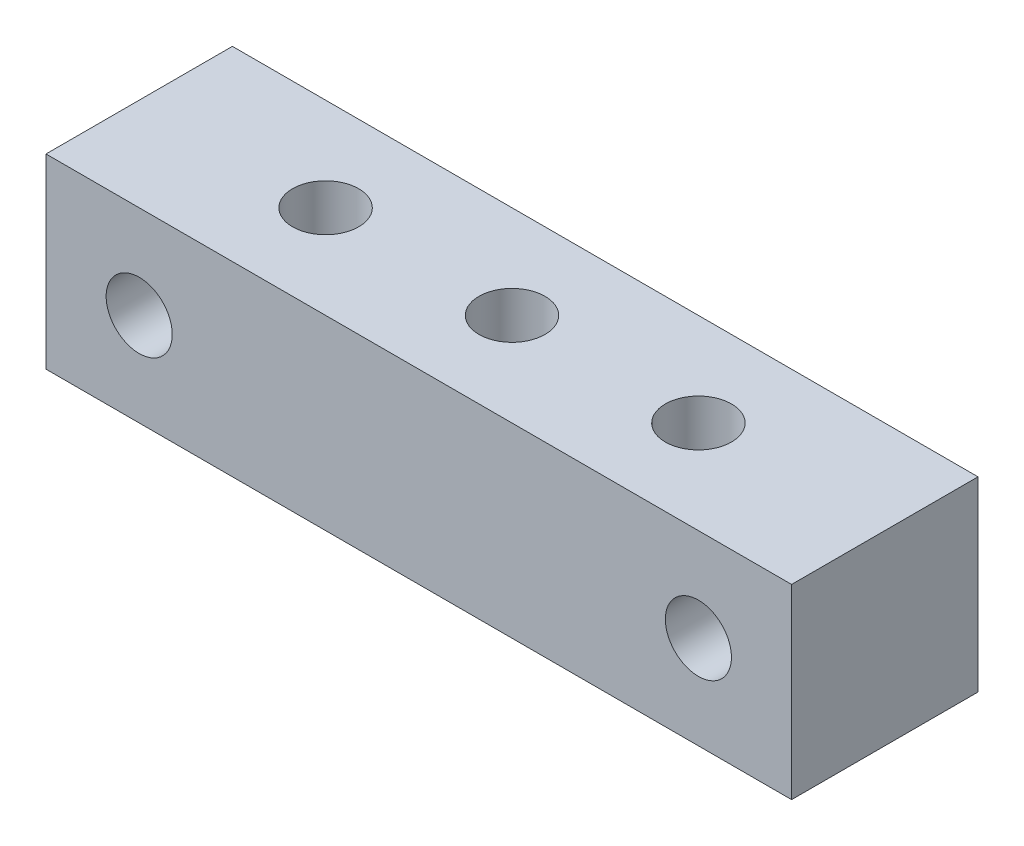
SolidWorks part; units mm, degrees
ref_plane "Front" through (0, 0, 0) normal (0, 0, 1) x (1, 0, 0)
ref_plane "Top" through (0, 0, 0) normal (0, 1, 0) x (1, 0, 0)
ref_plane "Right" through (0, 0, 0) normal (1, 0, 0) x (0, 0, -1)
sketch "Sketch1" plane through (0, 0, 0) normal (0, 0, 1) x (1, 0, 0)
  line L1 (-38.1, -9.525) -> (38.1, -9.525)
  line L2 (-38.1, -9.525) -> (-38.1, 9.525)
  line L3 (-38.1, 9.525) -> (38.1, 9.525)
  line L4 (38.1, -9.525) -> (38.1, 9.525)
  line L5 (-38.1, -9.525) -> (38.1, 9.525) construction
  line L6 (-38.1, 9.525) -> (38.1, -9.525) construction
  point P0 (0, 0)
  dimension "D1" = 19.05
  dimension "D2" = 76.2
extrude "Boss-Extrude1" add sketch "Sketch1" along normal blind 19.05
sketch "Sketch3" plane through (0, 0, 19.05) normal (0, 0, 1) x (1, 0, 0)
  line L1 (28.575, 0) -> (-28.575, 0) construction
  point P0 (0, 0)
  point P4 (0, 0)
  dimension "D2" = 57.15
hole_wizard "1/4 Clearance Hole1" positions "Sketch7" profile "Sketch6" hole size "1/4" standard "ANSI Inch" end condition through all
sketch "Sketch7" plane through (0, 0, 19.05) normal (0, 0, 1) x (1, 0, 0)
  point P0 (-28.575, 0)
  point P3 (28.575, 0)
sketch "Sketch6" plane through (-28.575, 0, 19.05) normal (1, 0, 0) x (0, -1, 0)
  line L0 (0, 0) -> (0, 19.05)
  line L1 (0, 19.05) -> (3.3782, 19.05)
  line L2 (3.3782, 19.05) -> (3.3782, 0)
  line L5 (3.3782, 0) -> (0, 0)
  line L11 (0, -6.35) -> (0, 107.95) construction
  dimension "Thru Hole Dia." = 6.7564
  dimension "Thru Hole Depth" = 19.05
sketch "Sketch8" plane through (0, 9.525, 0) normal (0, 1, 0) x (1, 0, 0)
  line L0 (0, 0) -> (0, -9.525) construction
  line L1 (38.1, 0) -> (-38.1, 0) construction
  line L2 (0, -9.525) -> (0, -19.05) construction
  line L3 (38.1, -19.05) -> (-38.1, -19.05) construction
  line L4 (0, -9.525) -> (19.05, -9.525) construction
  line L5 (0, -9.525) -> (-19.05, -9.525) construction
  dimension "D1" = 38.1
hole_wizard "1/4 Clearance Hole2" positions "Sketch10" profile "Sketch9" hole size "1/4" standard "ANSI Inch" end condition through all
sketch "Sketch10" plane through (0, 9.525, 0) normal (0, 1, 0) x (1, 0, 0)
  point P0 (0, -9.525)
  point P3 (-19.05, -9.525)
  point P6 (19.05, -9.525)
sketch "Sketch9" plane through (0, 9.525, 9.525) normal (1, 0, 0) x (0, 0, 1)
  line L0 (0, 0) -> (0, 19.05)
  line L1 (0, 19.05) -> (3.3782, 19.05)
  line L2 (3.3782, 19.05) -> (3.3782, 0)
  line L5 (3.3782, 0) -> (0, 0)
  line L11 (0, -6.35) -> (0, 107.95) construction
  dimension "Thru Hole Dia." = 6.7564
  dimension "Thru Hole Depth" = 19.05
